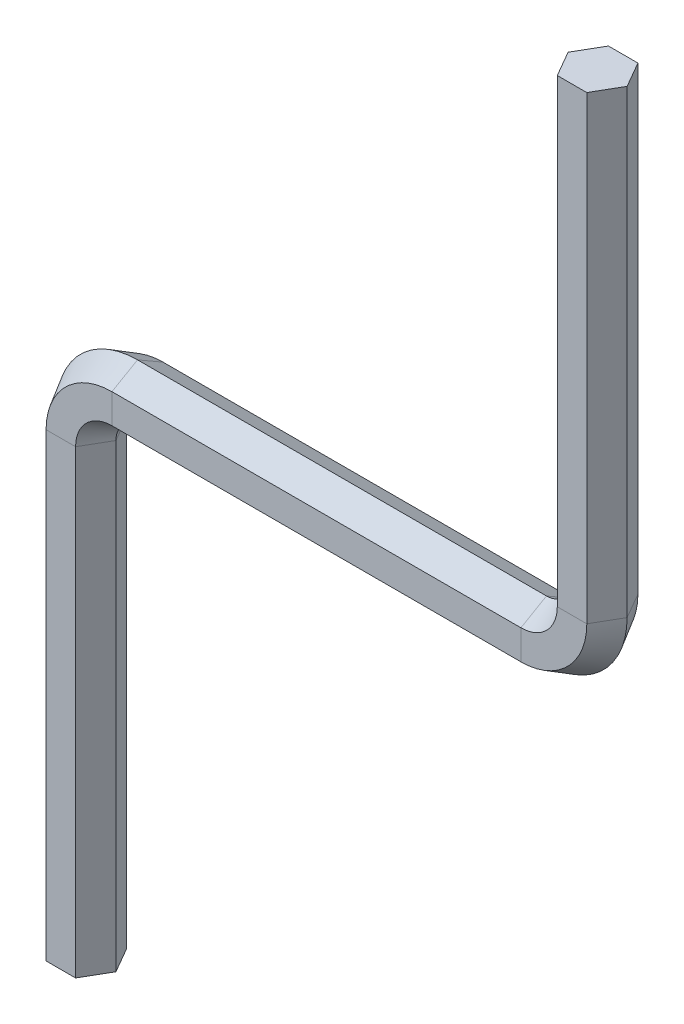
SolidWorks part; units mm, degrees
ref_plane "Front Plane" through (0, 0, 0) normal (0, 0, 1) x (1, 0, 0)
ref_plane "Top Plane" through (0, 0, 0) normal (0, 1, 0) x (1, 0, 0)
ref_plane "Right Plane" through (0, 0, 0) normal (1, 0, 0) x (0, 0, -1)
sketch "Sketch1" plane through (0, 0, 0) normal (0, 0, 1) x (1, 0, 0)
  line L0 (0, 0) -> (0, 450)
  line L1 (50, 500) -> (450, 500)
  line L2 (500, 550) -> (500, 1000)
  arc A0 (50, 500) -> (0, 450) centre (50, 450) ccw
  arc A1 (500, 550) -> (450, 500) centre (450, 550) cw
  point P7 (0, 500)
  point P10 (500, 500)
  dimension "D4" = 50
  dimension "D5" = 50
  dimension "D1" = 500
  dimension "D2" = 500
  dimension "D3" = 500
sketch "Sketch12" plane through (0, 0, 0) normal (0, 1, 0) x (1, 0, 0)
  line L1 (-14.4338, -25) -> (14.4338, -25)
  line L2 (14.4338, -25) -> (28.8675, 0)
  line L3 (28.8675, 0) -> (14.4338, 25)
  line L4 (14.4338, 25) -> (-14.4338, 25)
  line L5 (-14.4338, 25) -> (-28.8675, 0)
  line L6 (-28.8675, 0) -> (-14.4338, -25)
  circle A0 centre (0, 0) radius 25 construction
  dimension "D1" = 50
  dimension "D2" = 0
sweep "Sweep5" add profiles "Sketch12" path "Sketch1"
